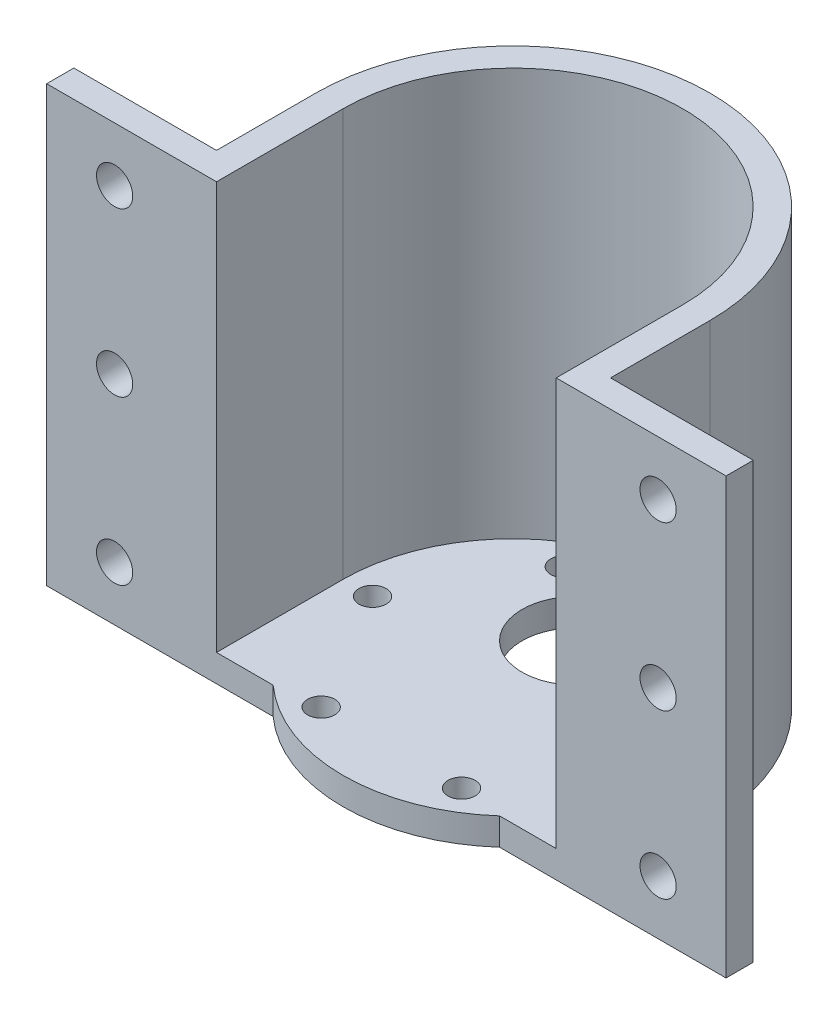
SolidWorks part; units mm, degrees
ref_plane "Front Plane" through (0, 0, 0) normal (0, 0, 1) x (1, 0, 0)
ref_plane "Top Plane" through (0, 0, 0) normal (0, 1, 0) x (1, 0, 0)
ref_plane "Right Plane" through (0, 0, 0) normal (1, 0, 0) x (0, 0, -1)
sketch "Sketch1" plane through (0, 0, 0) normal (0, 1, 0) x (1, 0, 0)
  line L0 (0, 0) -> (0, 35.7254) construction
  line L1 (0, 0) -> (37.5, 0) construction
  line L2 (37.5, 0) -> (12.5, 0)
  line L3 (-37.5, 0) -> (-37.5, 3)
  line L4 (-37.5, 3) -> (-21.75, 3)
  line L5 (-21.75, 3) -> (-21.75, 13.9754)
  line L6 (37.5, 0) -> (37.5, 3)
  line L7 (37.5, 3) -> (21.75, 3)
  line L8 (21.75, 3) -> (21.75, 13.9754)
  line L9 (-12.5, 0) -> (12.5, 0) construction
  line L10 (-12.5, 0) -> (-37.5, 0)
  arc A0 (-21.75, 13.9754) -> (21.75, 13.9754) centre (0, 13.9754) cw
  circle A1 centre (0, 13.9754) radius 18.75 construction
  arc A2 (-12.5, 0) -> (12.5, 0) centre (0, 13.9754) ccw
  dimension "D2" = 37.5
  dimension "D3" = 3
  dimension "D1" = 3
  dimension "D4" = 25
  dimension "D5" = 75
extrude "Boss-Extrude1" add sketch "Sketch1" along normal blind 48
sketch "Sketch2" plane through (0, 48, 0) normal (0, 1, 0) x (1, 0, 0)
  line L0 (0, 0) -> (0, 35.7254) construction
  line L1 (-18.75, 13.9754) -> (-18.75, 0)
  line L2 (12.5, 0) -> (37.5, 0) construction
  line L3 (-21.75, 13.9754) -> (-21.75, 3) construction
  line L4 (18.75, 13.9754) -> (18.75, 0)
  arc A0 (-18.75, 13.9754) -> (18.75, 13.9754) centre (0, 13.9754) cw
  arc A1 (21.75, 13.9754) -> (-21.75, 13.9754) centre (0, 13.9754) ccw construction
  dimension "D1" = 3
  dimension "D2" = 3
extrude "Cut-Extrude1" cut sketch "Sketch2" against normal blind 45 and the other way through all
sketch "Sketch3" plane through (0, 0, 0) normal (0, -1, 0) x (1, 0, 0)
  line L0 (0, 0) -> (0, -35.7254) construction
  line L1 (0, -13.9754) -> (15.5, -13.9754) construction
  arc A0 (-21.75, -13.9754) -> (21.75, -13.9754) centre (0, -13.9754) ccw construction
  circle A1 centre (0, -20.9754) radius 6
  circle A2 centre (15.5, -13.9754) radius 1.5
  circle A3 centre (7.75, -27.3988) radius 1.5
  circle A4 centre (-7.75, -27.3988) radius 1.5
  circle A5 centre (-15.5, -13.9754) radius 1.5
  circle A6 centre (-7.75, -0.552) radius 1.5
  circle A7 centre (7.75, -0.552) radius 1.5
  point P8 (0, -13.9754)
  point P26 (0, -13.9754)
  dimension "D1" = 7
  dimension "D2" = 12
  dimension "D3" = 3
  dimension "D4" = 15.5
  dimension "D5" = 6
extrude "Cut-Extrude2" cut sketch "Sketch3" against normal through all
sketch "Sketch4" plane through (0, 0, -3) normal (0, 0, -1) x (-1, 0, 0)
  line L0 (0, 0) -> (0, 48) construction
  line L1 (-21.75, 0) -> (21.75, 0) construction
  line L2 (21.75, 48) -> (-21.75, 48) construction
  line L3 (-30, 0) -> (-30, 48) construction
  line L4 (-37.5, 0) -> (-21.75, 0) construction
  line L5 (-37.5, 48) -> (-21.75, 48) construction
  line L6 (-37.5, 48) -> (-37.5, 0) construction
  circle A0 centre (-30, 6) radius 2
  circle A1 centre (-30, 24) radius 2
  circle A2 centre (-30, 42) radius 2
  circle A3 centre (30, 6) radius 2
  circle A4 centre (30, 24) radius 2
  circle A5 centre (30, 42) radius 2
  dimension "D1" = 4
  dimension "D3" = 18
  dimension "D4" = 18
  dimension "D2" = 7.5
extrude "Cut-Extrude3" cut sketch "Sketch4" against normal through all
